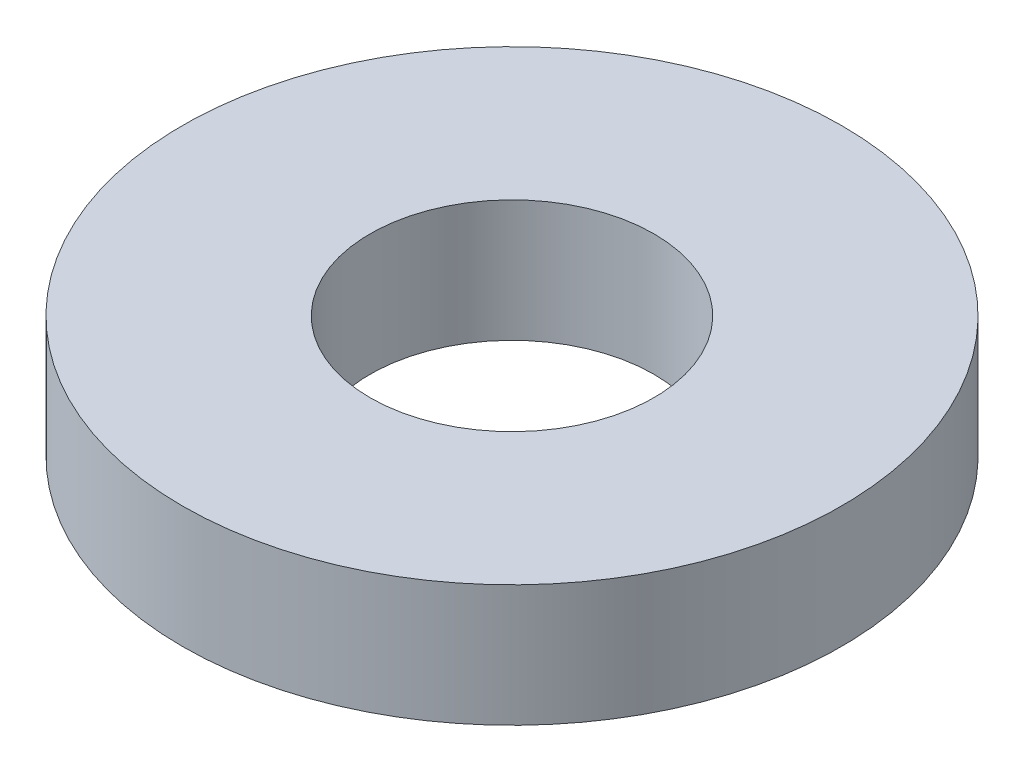
SolidWorks part; units mm, degrees
material "非常高密度 PE (SS)"
ref_plane "前视基准面" through (0, 0, 0) normal (0, 0, 1) x (1, 0, 0)
ref_plane "上视基准面" through (0, 0, 0) normal (0, 1, 0) x (1, 0, 0)
ref_plane "右视基准面" through (0, 0, 0) normal (1, 0, 0) x (0, 0, -1)
sketch "草图1" plane through (0, 0, 0) normal (0, 1, 0) x (1, 0, 0)
  circle A0 centre (0, 0) radius 14
  circle A1 centre (0, 0) radius 32.5
  dimension "D1" = 65
  dimension "D2" = 28
extrude "凸台-拉伸1" add sketch "草图1" along normal blind 12
